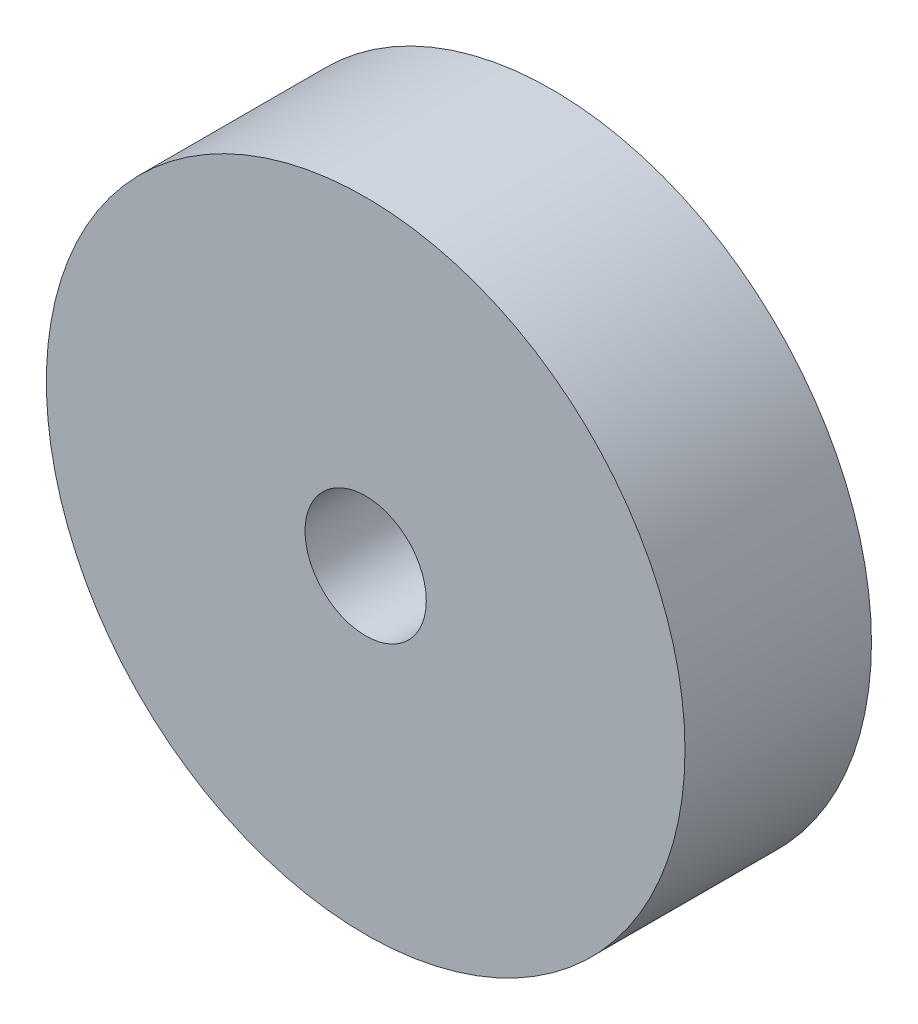
SolidWorks part; units mm, degrees
ref_plane "Front Plane" through (0, 0, 0) normal (0, 0, 1) x (1, 0, 0)
ref_plane "Top Plane" through (0, 0, 0) normal (0, 1, 0) x (1, 0, 0)
ref_plane "Right Plane" through (0, 0, 0) normal (1, 0, 0) x (0, 0, -1)
sketch "Sketch1" plane through (0, 0, 0) normal (0, 0, 1) x (1, 0, 0)
  circle A0 centre (0, 0) radius 13
  circle A1 centre (0, 0) radius 68.5
  dimension "D1" = 26
  dimension "D2" = 137
extrude "Boss-Extrude1" add sketch "Sketch1" along normal blind 40
